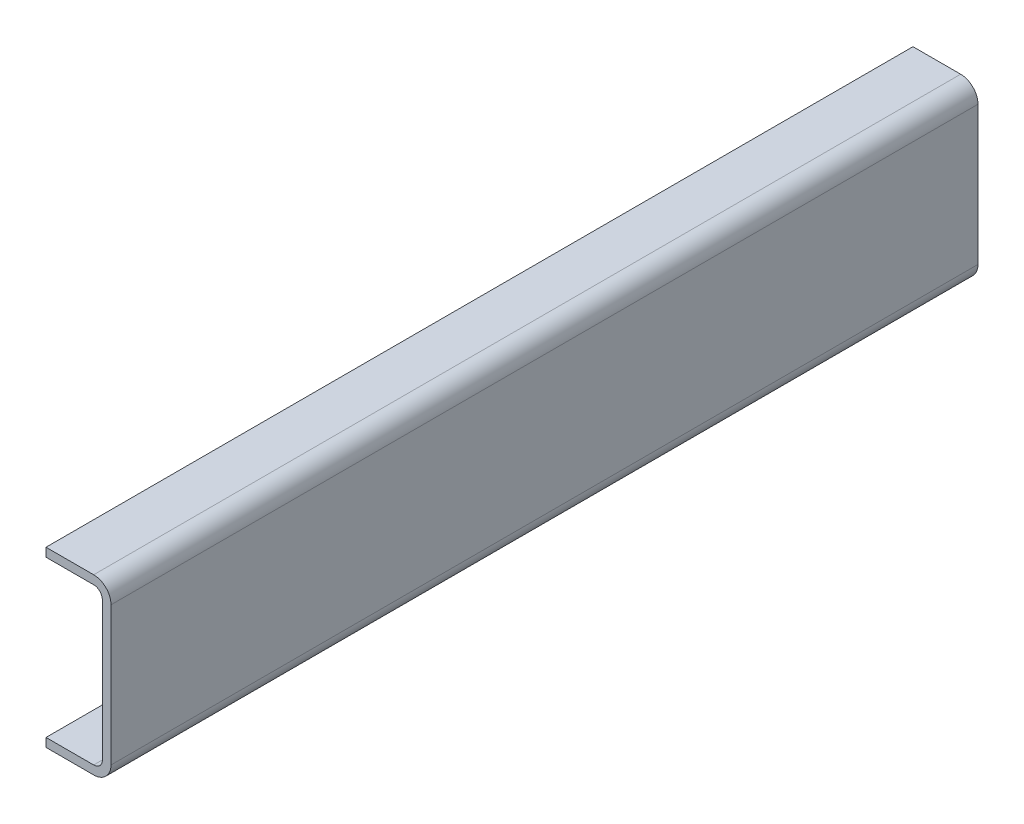
SolidWorks part; units mm, degrees
ref_plane "Front Plane" through (0, 0, 0) normal (0, 0, 1) x (1, 0, 0)
ref_plane "Top Plane" through (0, 0, 0) normal (0, 1, 0) x (1, 0, 0)
ref_plane "Right Plane" through (0, 0, 0) normal (1, 0, 0) x (0, 0, -1)
sketch "Sketch1" plane through (0, 0, 0) normal (0, 0, 1) x (1, 0, 0)
  line L0 (0, 2.54) -> (0, 22.86)
  line L1 (-2.54, 25.4) -> (-9.525, 25.4)
  line L2 (-2.54, 0) -> (-9.525, 0)
  line L3 (-2.54, 1.27) -> (-9.525, 1.27)
  line L4 (-1.27, 2.54) -> (-1.27, 22.86)
  line L5 (-2.54, 24.13) -> (-9.525, 24.13)
  line L6 (-9.525, 25.4) -> (-9.525, 24.13)
  line L7 (-9.525, 1.27) -> (-9.525, 0)
  arc A0 (0, 2.54) -> (-2.54, 0) centre (-2.54, 2.54) cw
  arc A1 (0, 22.86) -> (-2.54, 25.4) centre (-2.54, 22.86) ccw
  arc A2 (-1.27, 2.54) -> (-2.54, 1.27) centre (-2.54, 2.54) cw
  arc A3 (-1.27, 22.86) -> (-2.54, 24.13) centre (-2.54, 22.86) ccw
  point P7 (0, 0)
  point P10 (0, 25.4)
  dimension "D3" = 2.54
  dimension "D1" = 9.525
  dimension "D2" = 25.4
  dimension "D4" = 1.27
extrude "Boss-Extrude1" add sketch "Sketch1" along normal blind 127
equation "\"Length\"=4.5"
